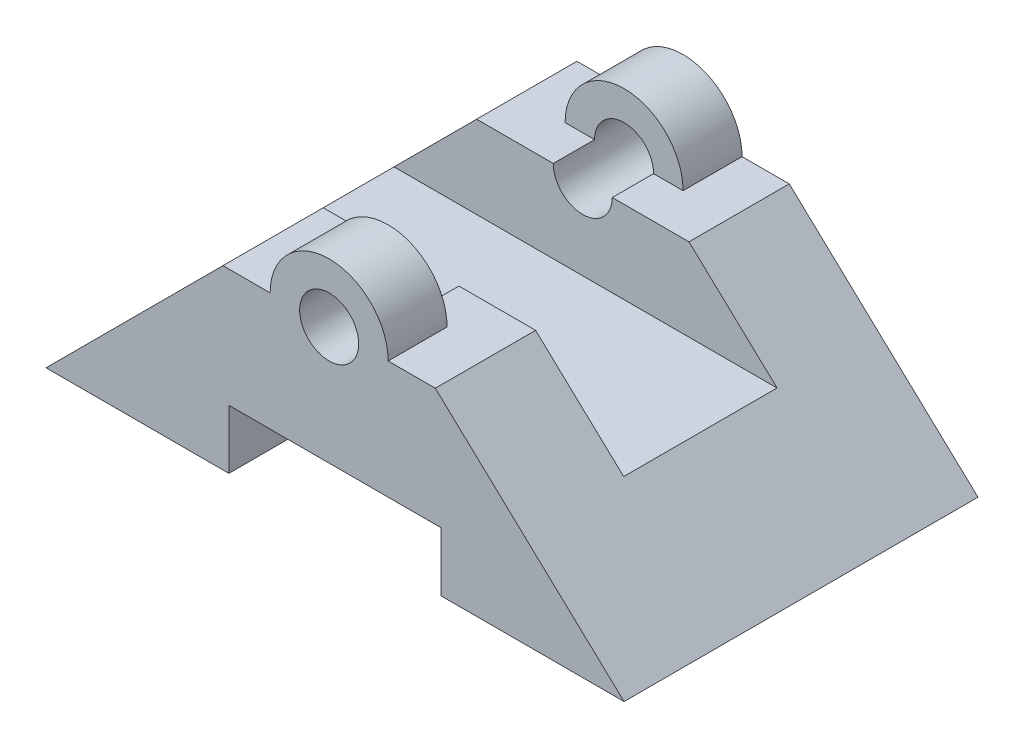
SolidWorks part; units mm, degrees
ref_plane "Front Plane" through (0, 0, 0) normal (0, 0, 1) x (1, 0, 0)
ref_plane "Top Plane" through (0, 0, 0) normal (0, 1, 0) x (1, 0, 0)
ref_plane "Right Plane" through (0, 0, 0) normal (1, 0, 0) x (0, 0, -1)
sketch "Sketch1" plane through (0, 0, 0) normal (0, 0, 1) x (1, 0, 0)
  line L0 (-35.2195, -14.8641) -> (-4.2195, -14.8641)
  line L1 (-35.2195, -14.8641) -> (-5.2195, 15.1359)
  line L2 (-5.2195, 15.1359) -> (4.7805, 15.1359)
  line L3 (-4.2195, -14.8641) -> (-4.2195, -4.8641)
  line L4 (-4.2195, -4.8641) -> (31.7805, -4.8641)
  line L5 (31.7805, -4.8641) -> (31.7805, -14.8641)
  line L6 (31.7805, -14.8641) -> (62.7805, -14.8641)
  line L7 (62.7805, -14.8641) -> (30.7805, 15.1359)
  line L8 (30.7805, 15.1359) -> (20.7805, 15.1359)
  line L9 (4.7805, 15.1359) -> (20.7805, 15.1359)
  dimension "D1" = 98
  dimension "D2" = 31
  dimension "D3" = 31
  dimension "D4" = 36
  dimension "D5" = 30
  dimension "D6" = 30
  dimension "D7" = 10
  dimension "D8" = 10
  dimension "D9" = 10
extrude "Boss-Extrude1" add sketch "Sketch1" against normal blind 17
sketch "Sketch2" plane through (0, 0, 0) normal (0, 0, 1) x (1, 0, 0)
  line L0 (30.7805, 15.1359) -> (-5.2195, 15.1359) construction
  line L1 (2.7805, 15.1359) -> (22.7805, 15.1359) construction
  line L2 (2.7805, 15.1359) -> (22.7805, 15.1359)
  circle A0 centre (12.7805, 15.1359) radius 10
  line M7 (30.7805, 15.1359) -> (-5.2195, 15.1359)
  dimension "D1" = 20
extrude "Boss-Extrude2" add sketch "Sketch2" against normal blind 10 contours A0 M7
sketch "Sketch3" plane through (0, 0, 0) normal (0, 0, 1) x (1, 0, 0)
  circle A0 centre (12.7805, 15.1359) radius 5
extrude "Cut-Extrude1" cut sketch "Sketch3" against normal blind 17
sketch "Sketch4" plane through (0, 0, -17) normal (0, 0, -1) x (-1, 0, 0)
  line L1 (-62.7805, -14.8641) -> (-45.7138, 1.1359)
  line L2 (-62.7805, -14.8641) -> (-30.7805, 15.1359) construction
  line L3 (-45.7138, 1.1359) -> (19.2195, 1.1359)
  line L4 (5.2195, 15.1359) -> (35.2195, -14.8641) construction
  line L5 (19.2195, 1.1359) -> (35.2195, -14.8641)
  line L6 (35.2195, -14.8641) -> (4.2195, -14.8641)
  line L7 (4.2195, -14.8641) -> (4.2195, -4.8641)
  line L8 (4.2195, -4.8641) -> (-31.7805, -4.8641)
  line L9 (-31.7805, -4.8641) -> (-31.7805, -14.8641)
  line L10 (-31.7805, -14.8641) -> (-62.7805, -14.8641)
  line L11 (-30.7805, 15.1359) -> (-17.7805, 15.1359) construction
  dimension "D1" = 14
extrude "Boss-Extrude3" add sketch "Sketch4" along normal blind 13
ref_plane "Plane2" through (0, 0, -30) normal (0, 0, -1) x (-1, 0, 0)
mirror "Mirror9" about plane through (0, 0, -30) normal (0, 0, -1) of bodies 106
